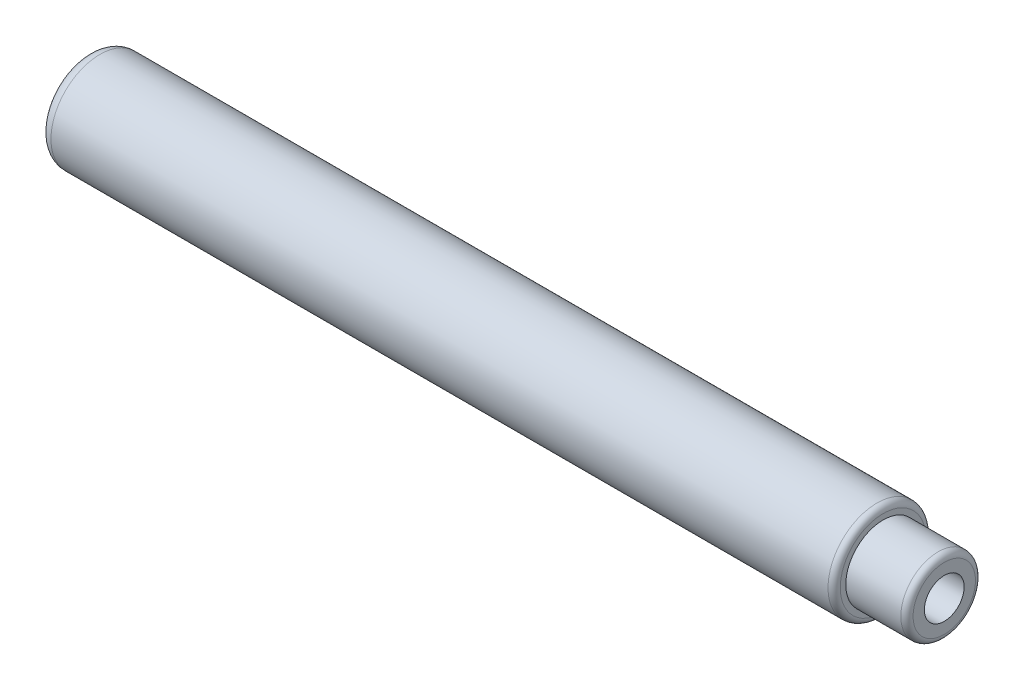
SolidWorks part; units mm, degrees
material "1.4003 (X2CrNi12)"
ref_plane "Ön Düzlem" through (0, 0, 0) normal (0, 0, 1) x (1, 0, 0)
ref_plane "Üst Düzlem" through (0, 0, 0) normal (0, 1, 0) x (1, 0, 0)
ref_plane "Sağ Düzlem" through (0, 0, 0) normal (1, 0, 0) x (0, 0, -1)
sketch "Çizim1" plane through (0, 0, 0) normal (0, 0, 1) x (1, 0, 0)
  line L5 (0, 0) -> (140, 0)
  line L6 (0, 0) -> (0, 8)
  line L7 (0, 8) -> (140, 8)
  line L8 (140, 0) -> (140, 8)
  dimension "D1" = 8
  dimension "D2" = 140
revolve "Döndür1" add sketch "Çizim1" angle 360 about L5
cosmetic thread "Kozmetik Diş Açma1" parameters "D2"=13.797
sketch "Çizim2" plane through (140, 0, 0) normal (1, 0, 0) x (0, 0, -1)
  circle A0 centre (0, 0) radius 8
  circle A1 centre (0, 0) radius 6.1
  circle A2 centre (0, 0) radius 8 construction
  dimension "D1" = 12.2
extrude "Kes-Ekstrüzyon1" cut sketch "Çizim2" against normal blind 10
sketch "Çizim3" plane through (140, 0, 0) normal (1, 0, 0) x (0, 0, -1)
  circle A0 centre (0, 0) radius 3.25
  dimension "D1" = 6.5
extrude "Kes-Ekstrüzyon2" cut sketch "Çizim3" against normal blind 10
cosmetic thread "Kozmetik Diş Açma2" parameters "D2"=8
fillet "Radyus1" radius 2 1 edges at (0, 0, 8)
fillet "Radyus2" radius 1 2 edges at (130, 0, -8) (140, 0, -6.1)
